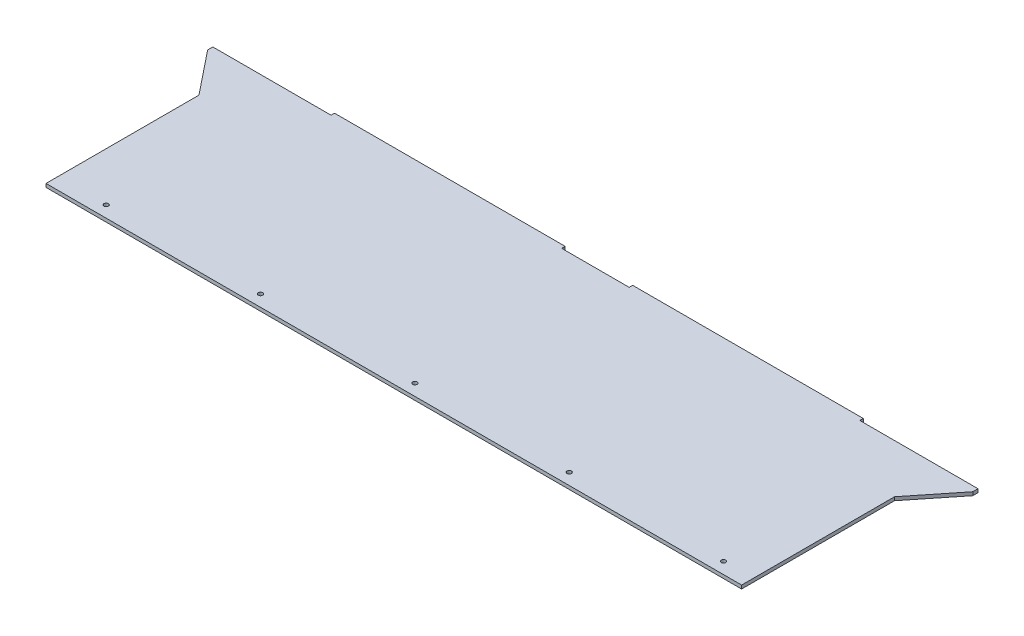
SolidWorks part; units mm, degrees
material "6061-T6 (SS)"
ref_plane "X-Y Datum" through (0, 0, 0) normal (0, 0, 1) x (1, 0, 0)
ref_plane "X-Z Datum" through (0, 0, 0) normal (0, 1, 0) x (1, 0, 0)
ref_plane "Y-Z Datum" through (0, 0, 0) normal (1, 0, 0) x (0, 0, -1)
sketch "Sketch1" plane through (0, 0, 0) normal (0, 1, 0) x (1, 0, 0)
  line L1 (-317.6778, 92.075) -> (317.6778, 92.075)
  line L2 (-317.6778, 92.075) -> (-317.6778, -92.075)
  line L3 (-317.6778, -92.075) -> (317.6778, -92.075)
  line L4 (317.6778, 92.075) -> (317.6778, -92.075)
  line L5 (-317.6778, 92.075) -> (317.6778, -92.075) construction
  line L6 (-317.6778, -92.075) -> (317.6778, 92.075) construction
  point P0 (0, 0)
  dimension "D1" = 635.3556
  dimension "D2" = 184.15
extrude "Boss-Extrude1" add sketch "Sketch1" along normal mid plane 3.175
sketch "Sketch2" plane through (0, 0, -92.075) normal (0, 0, -1) x (-1, 0, 0)
  line L0 (-241.4778, -1.5875) -> (-241.4778, 1.5875) construction
  line L1 (241.4778, -1.5875) -> (241.4778, 1.5875)
  line L2 (-241.4778, -1.5875) -> (-241.4778, 1.5875)
  line L3 (-241.4778, -1.5875) -> (-241.4778, 1.5875)
  line L4 (241.4778, -1.5875) -> (241.4778, 1.5875) construction
  line L5 (241.4778, -1.5875) -> (241.4778, 1.5875)
  line L20 (-317.6778, -1.5875) -> (317.6778, -1.5875) construction
  line L21 (-241.4778, -1.5875) -> (-30.8229, -1.5875)
  line L22 (30.8229, -1.5875) -> (241.4778, -1.5875)
  line L40 (30.8229, -1.5875) -> (30.8229, 1.5875)
  line L41 (30.8229, 1.5875) -> (241.4778, 1.5875)
  line L57 (-241.4778, 1.5875) -> (-30.8229, 1.5875)
  line L58 (-30.8229, 1.5875) -> (-30.8229, -1.5875)
  line M22 (-317.6778, -1.5875) -> (317.6778, -1.5875)
  line M24 (317.6778, 1.5875) -> (-317.6778, 1.5875)
extrude "Boss-Extrude2" add sketch "Sketch2" along normal blind 3.175 contours L58 L2 M24 M22 | L40 L1 M22 M24
sketch "Sketch3" plane through (0, 1.5875, 0) normal (0, 1, 0) x (1, 0, 0)
  line L0 (-317.6778, 92.075) -> (-349.4278, 92.075)
  line L1 (-349.4278, 92.075) -> (-349.4278, 87.3125)
  line L2 (-349.4278, 87.3125) -> (-317.6778, 47.625)
  line L3 (-317.6778, 92.075) -> (-317.6778, -92.075) construction
  line L16 (317.6778, -92.075) -> (317.6778, 92.075)
  line L17 (317.6778, 92.075) -> (241.4778, 92.075)
  line L18 (241.4778, 92.075) -> (241.4778, 95.25)
  line L19 (30.8229, 95.25) -> (30.8229, 92.075)
  line L20 (30.8229, 92.075) -> (-30.8229, 92.075)
  line L21 (-30.8229, 92.075) -> (-30.8229, 95.25)
  line L22 (-241.4778, 95.25) -> (-241.4778, 92.075)
  line L23 (-241.4778, 92.075) -> (-317.6778, 92.075)
  line L24 (241.4778, 95.25) -> (30.8229, 95.25)
  line L25 (241.4778, 95.25) -> (30.8229, 95.25)
  line L26 (-317.6778, 92.075) -> (-317.6778, -92.075)
  line L27 (-317.6778, -92.075) -> (317.6778, -92.075)
  line L38 (-317.6778, 92.075) -> (-317.6778, 47.625)
  line L40 (-30.8229, 95.25) -> (-241.4778, 95.25)
  line L41 (-30.8229, 95.25) -> (-241.4778, 95.25)
  line M26 (-317.6778, 92.075) -> (-317.6778, -92.075)
  dimension "D1" = 31.75
  dimension "D2" = 4.7625
  dimension "D3" = 44.45
  dimension "D4" = 0
extrude "Boss-Extrude3" add sketch "Sketch3" against normal blind 3.175 contours L1 L2 L0 M26
mirror "Mirror1" about plane through (0, 0, 0) normal (1, 0, 0) of "Boss-Extrude3"
sketch "Sketch4" plane through (0, 1.5875, 0) normal (0, 1, 0) x (1, 0, 0)
  line L0 (-273.2278, -92.075) -> (-273.2278, -81.534)
  line L1 (-317.6778, -92.075) -> (317.6778, -92.075) construction
  line L2 (-273.2278, -81.534) -> (-317.6778, -81.534)
  line L3 (-317.6778, 47.625) -> (-317.6778, -92.075) construction
  circle A0 centre (-273.2278, -81.534) radius 2.025
extrude "Cut-Extrude1" cut sketch "Sketch4" against normal blind 10 contours L0 A0 L2 | L2 A0 L0
pattern_linear "LPattern1" count 5 spacing 140.97 along (1, 0, 0) of "Cut-Extrude1"
